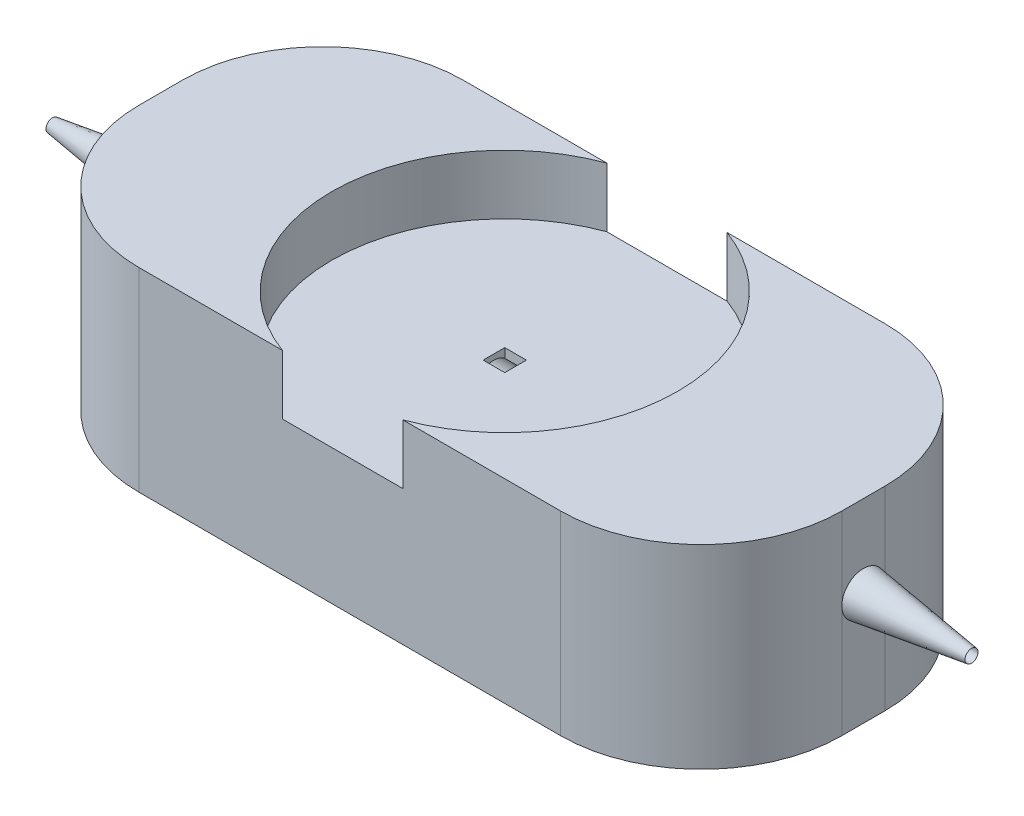
SolidWorks part; units mm, degrees
ref_plane "Front Plane" through (0, 0, 0) normal (0, 0, 1) x (1, 0, 0)
ref_plane "Top Plane" through (0, 0, 0) normal (0, 1, 0) x (1, 0, 0)
ref_plane "Right Plane" through (0, 0, 0) normal (1, 0, 0) x (0, 0, -1)
sketch "Sketch1" plane through (0, 0, 0) normal (0, 1, 0) x (1, 0, 0)
  line L1 (-25, -15) -> (40, -15)
  line L2 (-25, -15) -> (-25, 15)
  line L3 (-25, 15) -> (40, 15)
  line L4 (40, -15) -> (40, 15)
  line L5 (-25, -15) -> (40, 15) construction
  line L6 (-25, 15) -> (40, -15) construction
  point P0 (0, 0)
  dimension "D1" = 30
  dimension "D2" = 65
extrude "Boss-Extrude1" add sketch "Sketch1" along normal blind 58
sketch "Sketch3" plane through (-25, 0, 0) normal (-1, 0, 0) x (0, 0, 1)
  line L0 (-15, 58) -> (15, 58) construction
  circle A0 centre (0, 50.4) radius 1.6
  dimension "D1" = 3.2
  dimension "D2" = 7.6
fillet "Fillet1" radius 13 4 edges at (40, 29, -15) (-25, 29, -15) (40, 29, 15) (-25, 29, 15)
ref_plane "Plane2" through (0, -10, 0) normal (0, -1, 0) x (-1, 0, 0)
sketch "Sketch15" plane through (0, -10, 0) normal (0, -1, 0) x (-1, 0, 0)
  line L1 (-41.9055, 15.8797) -> (41.7906, 15.8797)
  line L2 (-41.9055, 15.8797) -> (-41.9055, -15.8187)
  line L3 (-41.9055, -15.8187) -> (41.7906, -15.8187)
  line L4 (41.7906, 15.8797) -> (41.7906, -15.8187)
extrude "Cut-Extrude7" cut sketch "Sketch15" against normal blind 50
ref_plane "Plane3" through (0, 40, 0) normal (0, -1, 0) x (-1, 0, 0)
ref_plane "Plane4" through (0, 58, 0) normal (0, 1, 0) x (1, 0, 0)
sketch "Sketch18" plane through (0, 58, 0) normal (0, 1, 0) x (1, 0, 0)
  circle A0 centre (6.8285, 0) radius 16
  dimension "D1" = 32
extrude "Cut-Extrude10" cut sketch "Sketch18" against normal blind 5.5
extrude "Cut-Extrude12" cut sketch "Sketch3" against normal up to next
ref_plane "Plane5" through (0, 52.5, 0) normal (0, 1, 0) x (1, 0, 0)
sketch "Sketch21" plane through (0, 52.5, 0) normal (0, 1, 0) x (1, 0, 0)
  line L1 (5.8285, -1) -> (7.8285, -1)
  line L2 (5.8285, -1) -> (5.8285, 1)
  line L3 (5.8285, 1) -> (7.8285, 1)
  line L4 (7.8285, -1) -> (7.8285, 1)
  line L5 (5.8285, -1) -> (7.8285, 1) construction
  line L6 (5.8285, 1) -> (7.8285, -1) construction
  point P0 (6.8285, 0)
  dimension "D1" = 2
  dimension "D2" = 2
extrude "Cut-Extrude13" cut sketch "Sketch21" against normal blind 8
ref_plane "Plane7" through (-25, 0, 0) normal (-1, 0, 0) x (0, 0, 1)
sketch "Sketch24" plane through (0, 0, 0) normal (0, 0, 1) x (1, 0, 0)
  line L0 (-25, 51) -> (-25, 52.4)
  line L1 (-25, 52) -> (-25, 48.8) construction
  line L2 (-25, 27.72) -> (-25, -27.72) construction
  line L3 (-25, 52.4) -> (-35, 51)
  line L4 (-35, 51) -> (-25, 51)
  line L5 (-25, 50.4) -> (-31.2466, 50.4) construction
  line L6 (-25, 40) -> (-25, 58) construction
  line L7 (-25, 50.4) -> (46.09, 50.4) construction
  dimension "D1" = 0.6
  dimension "D2" = 2
  dimension "D3" = 10
revolve "Revolve1" add sketch "Sketch24" angle 360 about L5
sketch "Sketch25" plane through (0, 0, 0) normal (0, 0, 1) x (1, 0, 0)
  line L4 (39.9952, 52.4) -> (49.9952, 51)
  line L5 (49.9952, 51) -> (39.9952, 51)
  line L6 (39.9952, 51) -> (39.9952, 52.4)
  line L7 (-25, 50.4) -> (46.09, 50.4) construction
  dimension "D1" = 0.6
  dimension "D2" = 2
  dimension "D3" = 10
revolve "Revolve2" add sketch "Sketch25" angle 360 about L7
